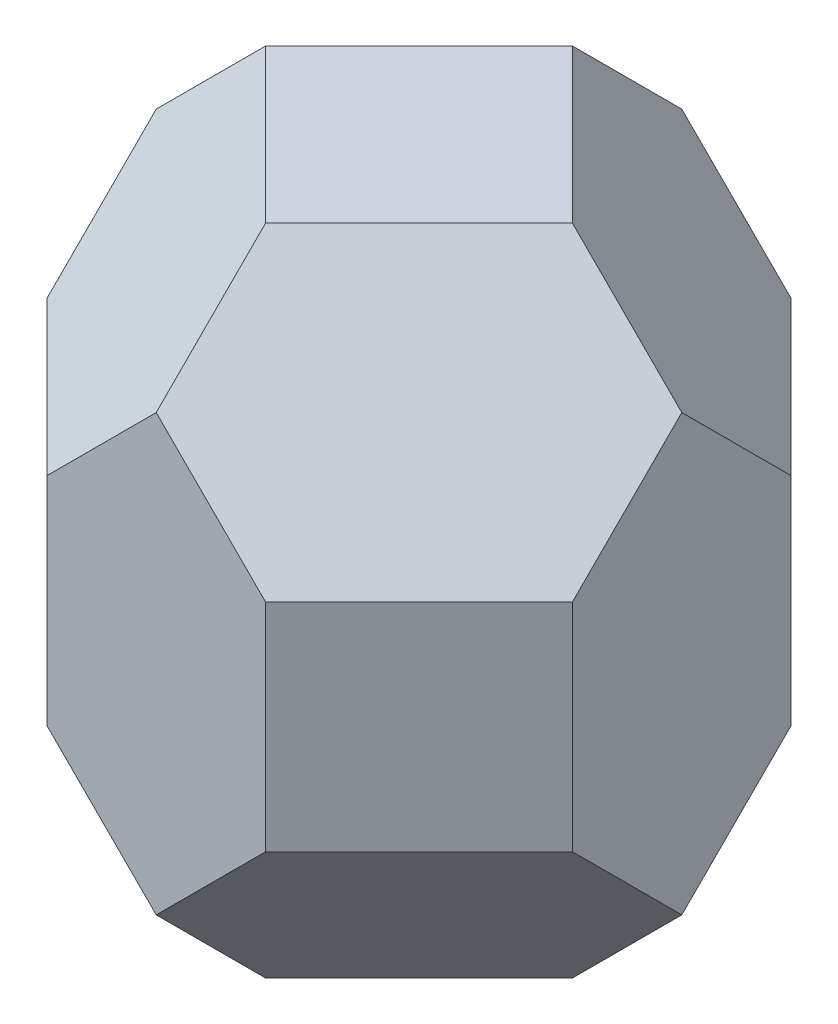
SolidWorks part; units mm, degrees
ref_plane "Front Plane" through (0, 0, 0) normal (0, 0, 1) x (1, 0, 0)
ref_plane "Top Plane" through (0, 0, 0) normal (0, 1, 0) x (1, 0, 0)
ref_plane "Right Plane" through (0, 0, 0) normal (1, 0, 0) x (0, 0, -1)
sketch "Sketch1" plane through (0, 0, 0) normal (0, 0, 1) x (1, 0, 0)
  line L0 (0, 0) -> (-35.3553, 35.3553)
  line L1 (-35.3553, 35.3553) -> (-35.3553, 105.3553)
  line L2 (-35.3553, 105.3553) -> (0, 140.7107)
  line L3 (0, 0) -> (0, 140.7107) construction
  line L4 (0, 0) -> (35.3553, 35.3553)
  line L5 (35.3553, 105.3553) -> (0, 140.7107)
  line L6 (35.3553, 35.3553) -> (35.3553, 105.3553)
  dimension "D1" = 50
  dimension "D2" = 70
  dimension "D3" = 50
  dimension "D4" = 135
  dimension "D5" = 135
extrude "Boss-Extrude1" add sketch "Sketch1" along normal blind 170
ref_plane "Plane3" through (0, 0, 0) normal (1, 0, 0) x (0, 0, -1)
sketch "Sketch2" plane through (0, 0, 0) normal (1, 0, 0) x (0, 0, -1)
  line L0 (-170, 35.3553) -> (-170, 105.3553) construction
  line L1 (-170, 105.3553) -> (0, 105.3553) construction
  line L2 (-170, 35.3553) -> (0, 35.3553) construction
  line L3 (0, 35.3553) -> (0, 105.3553) construction
  line L4 (-170, 35.3553) -> (-170, 105.3553)
  line L5 (-170, 105.3553) -> (0, 105.3553)
  line L6 (-170, 35.3553) -> (0, 35.3553)
  line L7 (0, 35.3553) -> (0, 105.3553)
  line L9 (-49.6447, 105.3553) -> (-85, 140.7107)
  line L10 (-120.3553, 105.3553) -> (-49.6447, 105.3553)
  line L11 (-120.3553, 105.3553) -> (-120.3553, 35.3553)
  line L12 (-120.3553, 35.3553) -> (-49.6447, 35.3553)
  line L13 (-49.6447, 105.3553) -> (-49.6447, 35.3553)
  line L15 (-49.6447, 35.3553) -> (-85, 0)
  line L16 (-120.3553, 105.3553) -> (-85, 140.7107)
  line L17 (-120.3553, 35.3553) -> (-85, 0)
  line L18 (-120.3553, 105.3553) -> (-120.3553, 35.3553)
  dimension "D1" = 49.6447
  dimension "D2" = 70.7107
  dimension "D3" = 135
extrude "Boss-Extrude2" add sketch "Sketch2" along normal mid plane 170 separate body contours L13 L5 L11 L6 | L16 L5 L9 | L6 L17 L15
ref_plane "Plane4" through (17.6777, 0, -17.6777) normal (0.7071, 0, -0.7071) x (-0.7071, 0, -0.7071)
sketch "Sketch3" plane through (17.6777, 0, -17.6777) normal (0.7071, 0, -0.7071) x (-0.7071, 0, -0.7071)
  line L0 (-95.2082, 105.3553) -> (-95.2082, 35.3553) construction
  line L1 (-25, 35.3553) -> (-25, 105.3553) construction
  line L2 (-95.2082, 105.3553) -> (-95.2082, 35.3553)
  line L3 (-25, 35.3553) -> (-25, 105.3553)
  line L4 (-95.2082, 105.3553) -> (-25, 105.3553)
  line L5 (-25, 35.3553) -> (-95.2082, 35.3553)
extrude "Boss-Extrude3" add sketch "Sketch3" against normal up to vertex (170.2082 mm away)
ref_plane "Plane5" through (0, 140.7107, 0) normal (0, 1, 0) x (1, 0, 0)
sketch "Sketch4" plane through (0, 140.7107, 0) normal (0, 1, 0) x (1, 0, 0)
  line L0 (35.3553, 0) -> (85, -49.6447) construction
  line L1 (85, -49.6447) -> (85, -85) construction
  line L2 (35.3553, 0) -> (0, 0) construction
  line L3 (35.3553, 0) -> (85, -49.6447)
  line L4 (85, -49.6447) -> (85, -85)
  line L5 (35.3553, 0) -> (0, 0)
  line L6 (85, -85) -> (0, 0) construction
  line L7 (0, -35.3553) -> (0, 0)
  line L8 (0, -35.3553) -> (49.6447, -85)
  line L9 (49.6447, -85) -> (85, -85)
  line L10 (0, -85) -> (-97.407, 12.407) construction
  line L11 (0, -35.3553) -> (-49.6447, -85)
  line L12 (0, -85) -> (24.8223, -60.1777) construction
  line L13 (49.6447, -85) -> (0, -134.6447)
  line L14 (-49.6447, -85) -> (0, -134.6447)
  point P13 (-24.8223, -60.1777)
  point P14 (24.8223, -109.8223)
extrude "Boss-Extrude7" add sketch "Sketch4" against normal up to vertex (140.7107 mm away) contours L11 L14 L13 L8 up to point (0, 0, 85)
ref_plane "Plane6" through (-17.6777, 0, -17.6777) normal (-0.7071, 0, -0.7071) x (-0.7071, 0, 0.7071)
sketch "Sketch5" plane through (-17.6777, 0, -17.6777) normal (-0.7071, 0, -0.7071) x (-0.7071, 0, 0.7071)
  line L0 (25, 105.3553) -> (25, 35.3553) construction
  line L1 (95.2082, 105.3553) -> (95.2082, 35.3553) construction
  line L2 (25, 105.3553) -> (25, 35.3553)
  line L3 (95.2082, 105.3553) -> (95.2082, 35.3553)
  line L4 (95.2082, 35.3553) -> (25, 35.3553)
  line L5 (25, 105.3553) -> (95.2082, 105.3553)
extrude "Boss-Extrude8" add sketch "Sketch5" against normal up to vertex (170.2082 mm away)
sketch "Sketch6" plane through (-17.6777, 0, -17.6777) normal (-0.7071, 0, -0.7071) x (-0.7071, 0, 0.7071)
  line L0 (95.2082, 35.3553) -> (120.2082, 0) construction
  line L1 (25, 35.3553) -> (0, 0) construction
  line L2 (95.2082, 35.3553) -> (120.2082, 0)
  line L3 (25, 35.3553) -> (0, 0)
  line L4 (95.2082, 105.3553) -> (25, 105.3553)
  line L5 (25, 105.3553) -> (25, 35.3553)
  line L6 (25, 35.3553) -> (95.2082, 35.3553)
  line L7 (95.2082, 35.3553) -> (95.2082, 105.3553)
  line L8 (95.2082, 105.3553) -> (25, 105.3553)
  line L9 (25, 105.3553) -> (25, 35.3553)
  line L10 (25, 35.3553) -> (95.2082, 35.3553)
  line L11 (95.2082, 35.3553) -> (95.2082, 105.3553)
  line L12 (120.2082, 0) -> (0, 0) construction
  dimension "D1" = 0
ref_plane "Plane7" through (0, 0, 0) normal (0.5774, 0.5774, 0.5774) x (0.8165, -0.4082, -0.4082)
sketch "Sketch7" plane through (0, 0, 0) normal (0.5774, 0.5774, 0.5774) x (0.8165, -0.4082, -0.4082)
  line L0 (-104.1033, -10.1041) -> (-104.1033, -60.1041) construction
  line L1 (-43.3013, 25) -> (0, 0) construction
  line L2 (-43.3013, 25) -> (-104.1033, -10.1041) construction
  line L3 (-104.1033, -10.1041) -> (-104.1033, -60.1041)
  line L4 (-43.3013, 25) -> (0, 0)
  line L5 (-43.3013, 25) -> (-104.1033, -10.1041)
  line L6 (-104.1033, -60.1041) -> (0, 0) construction
  line L7 (0, -50) -> (0, 0)
  line L8 (0, -50) -> (-60.802, -85.1041)
  line L9 (-60.802, -85.1041) -> (-104.1033, -60.1041)
extrude "Boss-Extrude9" add sketch "Sketch7" along normal blind 40
ref_plane "Plane8" through (0, 0, 0) normal (0.5774, -0.5774, -0.5774) x (-0.8165, -0.4082, -0.4082)
sketch "Sketch8" plane through (0, 0, 0) normal (0.5774, -0.5774, -0.5774) x (-0.8165, -0.4082, -0.4082)
  line L0 (0, 0) -> (-43.3013, 25) construction
  line L1 (-104.1033, -10.1041) -> (-43.3013, 25) construction
  line L2 (-104.1033, -10.1041) -> (-104.1033, -60.1041) construction
  line L3 (0, 0) -> (-43.3013, 25)
  line L4 (-104.1033, -10.1041) -> (-43.3013, 25)
  line L5 (-104.1033, -10.1041) -> (-104.1033, -60.1041)
  line L6 (0, 0) -> (-104.1033, -60.1041)
  line L7 (-60.802, -85.1041) -> (-104.1033, -60.1041)
  line L8 (-60.802, -85.1041) -> (0, -50)
  line L9 (0, 0) -> (0, -50)
extrude "Boss-Extrude10" add sketch "Sketch8" against normal blind 40 contours L6 L3 L4 L5 | L9 L6 L7 L8
ref_plane "Plane9" through (0, -35.3553, 0) normal (0, -1, 0) x (-1, 0, 0)
sketch "Sketch9" plane through (0, -35.3553, 0) normal (0, -1, 0) x (-1, 0, 0)
  line L0 (-49.6447, -85) -> (0, -35.3553) construction
  line L1 (49.6447, -85) -> (0, -35.3553) construction
  line L2 (-49.6447, -85) -> (0, -35.3553)
  line L3 (49.6447, -85) -> (0, -35.3553)
  line L4 (-24.8223, -60.1777) -> (33.6122, -118.6122) construction
  line L5 (24.8223, -60.1777) -> (-8.0968, -93.0968) construction
  line L6 (0, -134.6447) -> (49.6447, -85)
  line L7 (-49.6447, -85) -> (0, -134.6447)
extrude "Boss-Extrude11" add sketch "Sketch9" against normal blind 40
ref_plane "Plane11" through (-56.6667, -56.6667, 56.6667) normal (-0.5774, -0.5774, 0.5774) x (0.8165, -0.4082, 0.4082)
sketch "Sketch11" plane through (-56.6667, -56.6667, 56.6667) normal (-0.5774, -0.5774, 0.5774) x (0.8165, -0.4082, 0.4082)
  line L0 (26.1009, 145.2082) -> (69.4022, 120.2082) construction
  line L1 (26.1009, 145.2082) -> (-34.7011, 110.1041) construction
  line L2 (-34.7011, 110.1041) -> (-34.7011, 60.1041) construction
  line L3 (26.1009, 145.2082) -> (69.4022, 120.2082)
  line L4 (26.1009, 145.2082) -> (-34.7011, 110.1041)
  line L5 (-34.7011, 110.1041) -> (-34.7011, 60.1041)
  line L6 (-34.7011, 60.1041) -> (69.4022, 120.2082)
  line L7 (8.6002, 35.1041) -> (-34.7011, 60.1041)
  line L8 (69.4022, 70.2082) -> (8.6002, 35.1041)
  line L9 (69.4022, 70.2082) -> (69.4022, 120.2082)
extrude "Boss-Extrude14" add sketch "Sketch11" against normal blind 40 contours L5 L6 L3 L4 | L8 L9 L6 L7
ref_plane "Plane12" through (56.6667, -56.6667, 56.6667) normal (0.5774, -0.5774, 0.5774) x (0.4082, -0.4082, -0.8165)
sketch "Sketch12" plane through (56.6667, -56.6667, 56.6667) normal (0.5774, -0.5774, 0.5774) x (0.4082, -0.4082, -0.8165)
  line L0 (-78.0024, 85.1041) -> (-138.8044, 50) construction
  line L1 (-138.8044, 0) -> (-138.8044, 50) construction
  line L2 (-95.5031, -25) -> (-138.8044, 0) construction
  line L3 (-34.7011, 10.1041) -> (-95.5031, -25) construction
  line L4 (-34.7011, 10.1041) -> (-34.7011, 60.1041) construction
  line L5 (-78.0024, 85.1041) -> (-34.7011, 60.1041) construction
  line L6 (-78.0024, 85.1041) -> (-138.8044, 50)
  line L7 (-138.8044, 0) -> (-138.8044, 50)
  line L8 (-95.5031, -25) -> (-138.8044, 0)
  line L9 (-34.7011, 10.1041) -> (-95.5031, -25)
  line L10 (-34.7011, 10.1041) -> (-34.7011, 60.1041)
  line L11 (-78.0024, 85.1041) -> (-34.7011, 60.1041)
extrude "Boss-Extrude15" add sketch "Sketch12" against normal blind 40
ref_plane "Plane13" through (-46.9036, 46.9036, -46.9036) normal (0.5774, -0.5774, 0.5774) x (0.4082, -0.4082, -0.8165)
sketch "Sketch13" plane through (-46.9036, 46.9036, -46.9036) normal (0.5774, -0.5774, 0.5774) x (0.4082, -0.4082, -0.8165)
  line L0 (-118.2469, 14.3934) -> (-57.4449, 49.4975) construction
  line L1 (-118.2469, 14.3934) -> (-161.5482, 39.3934) construction
  line L2 (-147.1145, 64.3934) -> (-161.5482, 39.3934) construction
  line L3 (-86.3124, 99.4975) -> (-147.1145, 64.3934) construction
  line L4 (-86.3124, 99.4975) -> (-57.4449, 99.4975) construction
  line L5 (-57.4449, 99.4975) -> (-57.4449, 49.4975) construction
  line L6 (-118.2469, 14.3934) -> (-57.4449, 49.4975)
  line L7 (-118.2469, 14.3934) -> (-161.5482, 39.3934)
  line L8 (-147.1145, 64.3934) -> (-161.5482, 39.3934)
  line L9 (-86.3124, 99.4975) -> (-147.1145, 64.3934)
  line L10 (-86.3124, 99.4975) -> (-57.4449, 99.4975)
  line L11 (-57.4449, 99.4975) -> (-57.4449, 49.4975)
ref_plane "Plane14" through (103.5702, 103.5702, 103.5702) normal (-0.5774, -0.5774, -0.5774) x (-0.8165, 0.4082, 0.4082)
sketch "Sketch14" plane through (103.5702, 103.5702, 103.5702) normal (-0.5774, -0.5774, -0.5774) x (-0.8165, 0.4082, 0.4082)
  line L0 (83.5458, -45.7107) -> (126.8471, -20.7107) construction
  line L1 (22.7438, -10.6066) -> (22.7438, 39.3934) construction
  line L2 (83.5458, -45.7107) -> (22.7438, -10.6066) construction
  line L3 (83.5458, -45.7107) -> (126.8471, -20.7107)
  line L4 (22.7438, -10.6066) -> (22.7438, 39.3934)
  line L5 (83.5458, -45.7107) -> (22.7438, -10.6066)
  line L6 (22.7438, 39.3934) -> (126.8471, -20.7107)
  line L7 (126.8471, 29.2893) -> (126.8471, -20.7107)
  line L8 (126.8471, 29.2893) -> (66.0451, 64.3934)
  line L9 (66.0451, 64.3934) -> (22.7438, 39.3934)
extrude "Boss-Extrude17" add sketch "Sketch14" along normal blind 40 contours L6 L4 L5 L3 | L8 L9 L6 L7
ref_plane "Plane15" through (-103.5702, 103.5702, 103.5702) normal (-0.5774, 0.5774, 0.5774) x (0.8165, 0.4082, 0.4082)
sketch "Sketch15" plane through (-103.5702, 103.5702, 103.5702) normal (-0.5774, 0.5774, 0.5774) x (0.8165, 0.4082, 0.4082)
  line L0 (22.7438, -10.6066) -> (22.7438, 39.3934) construction
  line L1 (126.8471, -20.7107) -> (83.5458, -45.7107) construction
  line L2 (22.7438, -10.6066) -> (83.5458, -45.7107) construction
  line L3 (22.7438, -10.6066) -> (22.7438, 39.3934)
  line L4 (126.8471, -20.7107) -> (83.5458, -45.7107)
  line L5 (22.7438, -10.6066) -> (83.5458, -45.7107)
  line L6 (126.8471, -20.7107) -> (22.7438, 39.3934)
  line L7 (126.8471, -20.7107) -> (126.8471, 29.2893)
  line L8 (66.0451, 64.3934) -> (126.8471, 29.2893)
  line L9 (66.0451, 64.3934) -> (22.7438, 39.3934)
extrude "Boss-Extrude20" add sketch "Sketch15" against normal blind 40 contours L4 L6 L3 L5 | L8 L9 L6 L7
ref_plane "Plane18" through (0, 176.066, 0) normal (0, 1, 0) x (1, 0, 0)
sketch "Sketch18" plane through (0, 176.066, 0) normal (0, 1, 0) x (1, 0, 0)
  line L0 (-49.6447, -85) -> (0, -134.6447) construction
  line L1 (0, -134.6447) -> (49.6447, -85) construction
  line L2 (-49.6447, -85) -> (0, -134.6447)
  line L3 (0, -134.6447) -> (49.6447, -85)
  line L4 (49.6447, -85) -> (-49.6447, -85)
  line L5 (0, -35.3553) -> (49.6447, -85)
  line L6 (-49.6447, -85) -> (0, -35.3553)
extrude "Boss-Extrude21" add sketch "Sketch18" against normal blind 40 contours L3 L4 L2 | L6 L4 L5
ref_plane "Plane19" through (46.9036, 46.9036, -46.9036) normal (-0.5774, -0.5774, 0.5774) x (-0.8165, 0.4082, -0.4082)
sketch "Sketch19" plane through (46.9036, 46.9036, -46.9036) normal (-0.5774, -0.5774, 0.5774) x (-0.8165, 0.4082, -0.4082)
  line L0 (14.1436, -74.4975) -> (-46.6584, -109.6016) construction
  line L1 (14.1436, -74.4975) -> (57.4449, -99.4975) construction
  line L2 (-46.6584, -109.6016) -> (-46.6584, -159.6016) construction
  line L3 (57.4449, -149.4975) -> (-3.3572, -184.6016) construction
  line L4 (-3.3572, -184.6016) -> (-46.6584, -159.6016) construction
  line L6 (14.1436, -74.4975) -> (-46.6584, -109.6016)
  line L7 (14.1436, -74.4975) -> (57.4449, -99.4975)
  line L8 (-46.6584, -109.6016) -> (-46.6584, -159.6016)
  line L9 (57.4449, -149.4975) -> (-3.3572, -184.6016)
  line L10 (-3.3572, -184.6016) -> (-46.6584, -159.6016)
  line L11 (57.4449, -149.4975) -> (57.4449, -99.4975)
extrude "Boss-Extrude22" add sketch "Sketch19" along normal blind 40
ref_plane "Plane20" through (-46.9036, 46.9036, -46.9036) normal (-0.5774, 0.5774, -0.5774) x (-0.4082, 0.4082, 0.8165)
sketch "Sketch20" plane through (-46.9036, 46.9036, -46.9036) normal (-0.5774, 0.5774, -0.5774) x (-0.4082, 0.4082, 0.8165)
  line L0 (161.5482, 89.3934) -> (161.5482, 39.3934) construction
  line L1 (118.2469, 14.3934) -> (161.5482, 39.3934) construction
  line L2 (118.2469, 14.3934) -> (57.4449, 49.4975) construction
  line L3 (100.7462, 124.4975) -> (57.4449, 99.4975) construction
  line L4 (161.5482, 89.3934) -> (100.7462, 124.4975) construction
  line L5 (57.4449, 99.4975) -> (57.4449, 49.4975) construction
  line L6 (161.5482, 89.3934) -> (161.5482, 39.3934)
  line L7 (118.2469, 14.3934) -> (161.5482, 39.3934)
  line L8 (118.2469, 14.3934) -> (57.4449, 49.4975)
  line L9 (100.7462, 124.4975) -> (57.4449, 99.4975)
  line L10 (161.5482, 89.3934) -> (100.7462, 124.4975)
  line L11 (57.4449, 99.4975) -> (57.4449, 49.4975)
ref_plane "Plane21" through (-46.9036, 46.9036, -46.9036) normal (-0.5774, 0.5774, -0.5774) x (-0.4082, 0.4082, 0.8165)
sketch "Sketch21" plane through (-46.9036, 46.9036, -46.9036) normal (-0.5774, 0.5774, -0.5774) x (-0.4082, 0.4082, 0.8165)
  line L0 (161.5482, 89.3934) -> (100.7462, 124.4975) construction
  line L1 (100.7462, 124.4975) -> (57.4449, 99.4975) construction
  line L2 (57.4449, 99.4975) -> (57.4449, 49.4975) construction
  line L3 (118.2469, 14.3934) -> (57.4449, 49.4975) construction
  line L4 (118.2469, 14.3934) -> (161.5482, 39.3934) construction
  line L5 (161.5482, 89.3934) -> (161.5482, 39.3934) construction
  line L6 (161.5482, 89.3934) -> (100.7462, 124.4975)
  line L7 (100.7462, 124.4975) -> (57.4449, 99.4975)
  line L8 (57.4449, 99.4975) -> (57.4449, 49.4975)
  line L9 (118.2469, 14.3934) -> (57.4449, 49.4975)
  line L10 (118.2469, 14.3934) -> (161.5482, 39.3934)
  line L11 (161.5482, 89.3934) -> (161.5482, 39.3934)
extrude "Boss-Extrude24" add sketch "Sketch21" against normal blind 40
